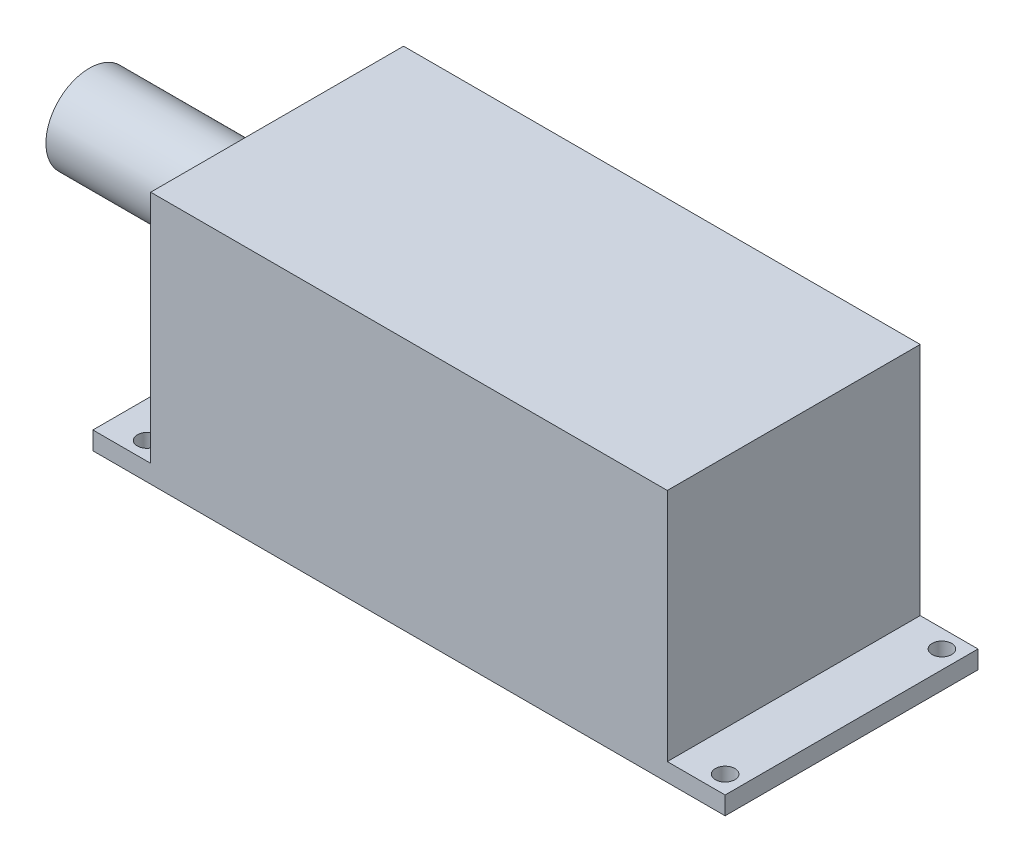
SolidWorks part; units mm, degrees
ref_plane "Front Plane" through (0, 0, 0) normal (0, 0, 1) x (1, 0, 0)
ref_plane "Top Plane" through (0, 0, 0) normal (0, 1, 0) x (1, 0, 0)
ref_plane "Right Plane" through (0, 0, 0) normal (1, 0, 0) x (0, 0, -1)
sketch "Sketch1" plane through (0, 0, 0) normal (0, 1, 0) x (1, 0, 0)
  line L1 (-111.125, -44.45) -> (111.125, -44.45)
  line L2 (-111.125, -44.45) -> (-111.125, 44.45)
  line L3 (-111.125, 44.45) -> (111.125, 44.45)
  line L4 (111.125, -44.45) -> (111.125, 44.45)
  line L5 (-111.125, -44.45) -> (111.125, 44.45) construction
  line L6 (-111.125, 44.45) -> (111.125, -44.45) construction
  point P0 (0, 0)
  dimension "D1" = 222.25
  dimension "D2" = 88.9
extrude "Boss-Extrude1" add sketch "Sketch1" along normal blind 88.9
sketch "Sketch4" plane through (0, 88.9, 0) normal (0, 1, 0) x (1, 0, 0)
  line L0 (-111.125, -44.45) -> (111.125, -44.45) construction
  line L1 (-111.125, 44.45) -> (-90.805, 44.45)
  line L2 (-111.125, 44.45) -> (-111.125, -44.45)
  line L3 (-111.125, -44.45) -> (-90.805, -44.45)
  line L4 (-90.805, 44.45) -> (-90.805, -44.45)
  line L6 (111.125, 44.45) -> (90.805, 44.45)
  line L7 (111.125, 44.45) -> (111.125, -44.45)
  line L8 (111.125, -44.45) -> (90.805, -44.45)
  line L9 (90.805, 44.45) -> (90.805, -44.45)
  dimension "D1" = 20.32
extrude "Cut-Extrude1" cut sketch "Sketch4" against normal offset from surface (82.55 mm away) 6.35 up to face at (0, 0, 0)
ref_plane "Plane1" through (0, 56.1594, 0) normal (0, 1, 0) x (1, 0, 0)
sketch "Sketch2" plane through (0, 56.1594, 0) normal (0, 1, 0) x (1, 0, 0)
  line L0 (0, 0) -> (-156.845, 0)
  line L2 (-156.845, 0) -> (-156.845, 15.24)
  line L3 (-156.845, 15.24) -> (0, 15.24)
  line L4 (0, 15.24) -> (0, 0)
  line L6 (-90.805, -44.45) -> (-90.805, 44.45) construction
  dimension "D1" = 15.24
  dimension "D2" = 66.04
revolve "Revolve1" add sketch "Sketch2" angle 360 about L0
sketch "Sketch5" plane through (0, 6.35, 0) normal (0, 1, 0) x (1, 0, 0)
  line L0 (-90.805, 44.45) -> (-111.125, 44.45) construction
  line L1 (-111.125, 44.45) -> (-111.125, -44.45) construction
  circle A0 centre (-98.425, 38.1) radius 3.429
  circle A1 centre (104.775, 38.1) radius 3.429
  circle A2 centre (104.775, -38.1) radius 3.429
  circle A3 centre (-98.425, -38.1) radius 3.429
  dimension "D1" = 6.858
  dimension "D2" = 6.35
  dimension "D3" = 12.7
  dimension "D4" = 2
  dimension "D5" = 2
extrude "Cut-Extrude2" cut sketch "Sketch5" against normal through all
